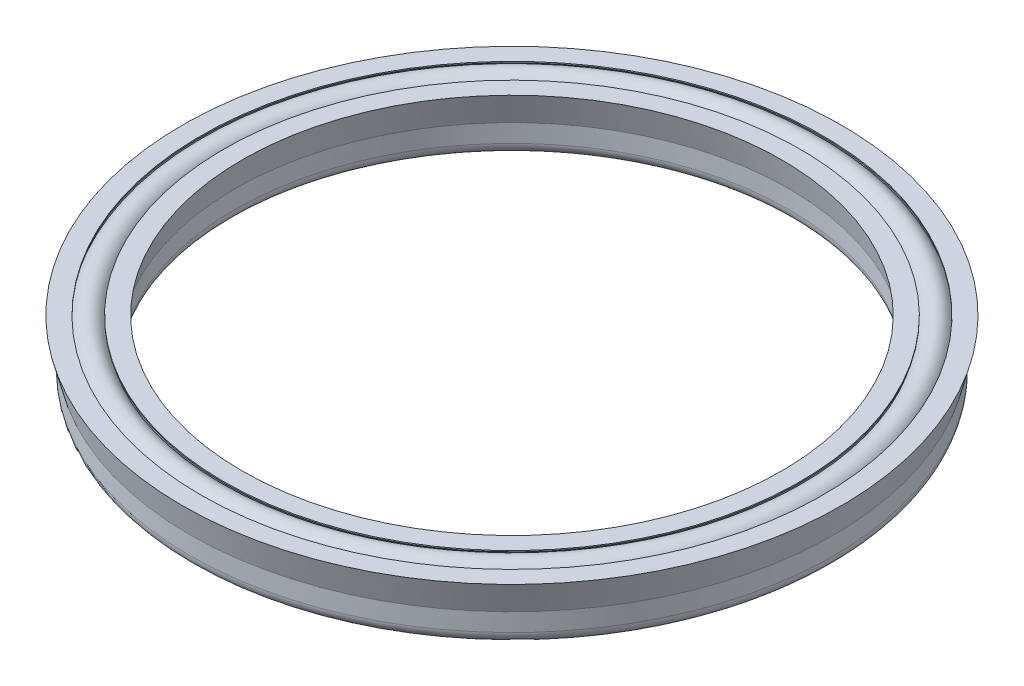
SolidWorks part; units mm, degrees
material "Neoprene Rubber-60A Durometer"
ref_plane "Front Plane" through (0, 0, 0) normal (0, 0, 1) x (1, 0, 0)
ref_plane "Top Plane" through (0, 0, 0) normal (0, 1, 0) x (1, 0, 0)
ref_plane "Right Plane" through (0, 0, 0) normal (1, 0, 0) x (0, 0, -1)
sketch "Sketch1" plane through (0, 0, 0) normal (0, 0, 1) x (1, 0, 0)
  line L0 (0, 0) -> (0, -9.4095) construction
  line L1 (0, 0) -> (-28.575, 0) construction
  line L5 (-32.8612, -6.2484) -> (-30.6387, -6.2484)
  line L6 (-34.925, 0) -> (-32.9711, 0)
  line L7 (-34.1312, -3.0734) -> (-34.1312, -4.9784)
  line L8 (-29.3687, -3.0734) -> (-29.3687, -4.9784)
  line L9 (-34.1312, -3.0734) -> (-34.925, 0)
  line L10 (-29.3687, -3.0734) -> (-28.575, 0)
  line L11 (-32.9711, -0.1217) -> (-32.9711, 0)
  line L12 (-30.5288, -0.1217) -> (-30.5288, 0)
  line L13 (-30.5288, 0) -> (-28.575, 0)
  arc A0 (-32.9711, -0.1217) -> (-30.5288, -0.1217) centre (-31.75, -1.1361) ccw
  arc A1 (-34.1312, -4.9784) -> (-32.8612, -6.2484) centre (-32.8612, -4.9784) ccw
  arc A2 (-30.6387, -6.2484) -> (-29.3687, -4.9784) centre (-30.6387, -4.9784) ccw
  circle A3 centre (-31.75, -1.1361) radius 1.4684
  dimension "D1" = 57.15
  dimension "D2" = 6.35
revolve "Revolve1" add sketch "Sketch1" angle 360 about L0
